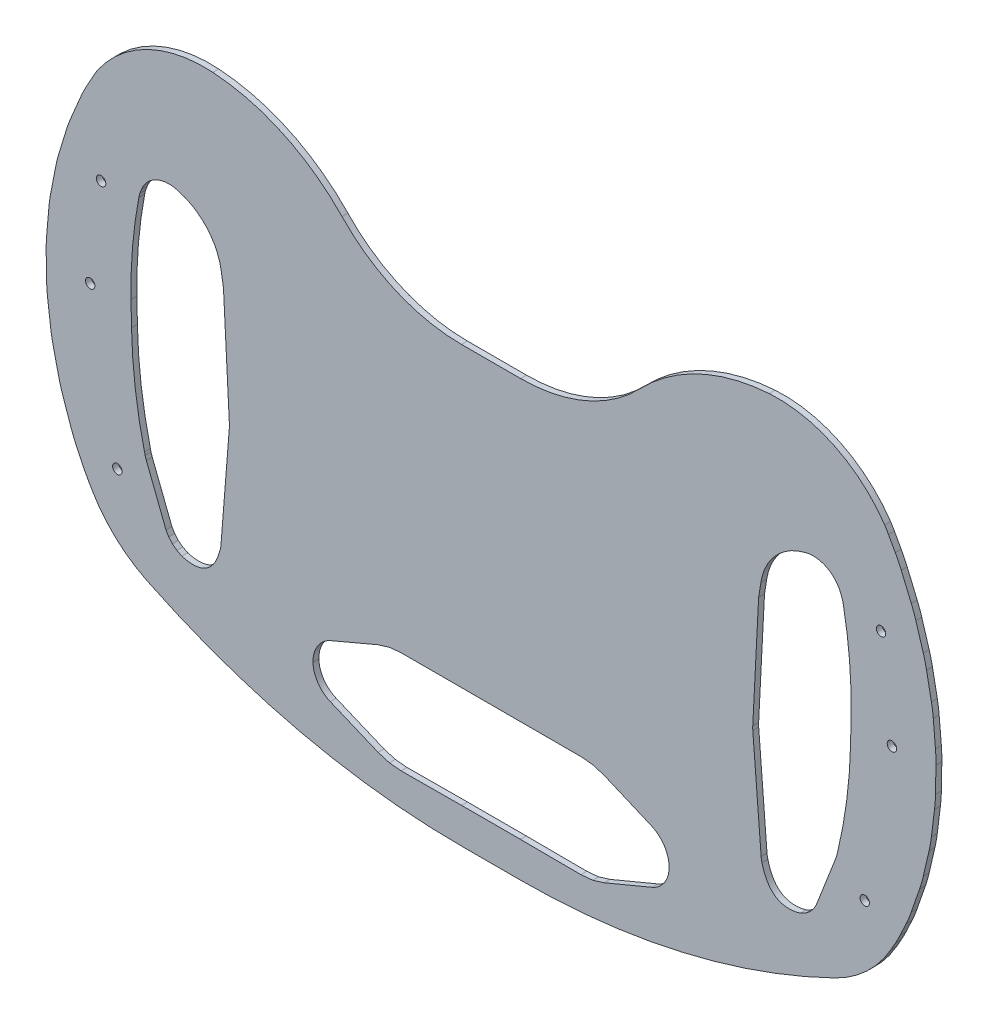
SolidWorks part; units mm, degrees
ref_plane "Front Plane" through (0, 0, 0) normal (0, 0, 1) x (1, 0, 0)
ref_plane "Top Plane" through (0, 0, 0) normal (0, 1, 0) x (1, 0, 0)
ref_plane "Right Plane" through (0, 0, 0) normal (1, 0, 0) x (0, 0, -1)
ref_plane "Plane1" through (0, 0, 3.5) normal (0, 0, -1) x (-1, 0, 0)
sketch "Sketch1" plane through (0, 0, 3.5) normal (0, 0, -1) x (-1, 0, 0)
  line L0 (-20, -102.6414) -> (0, -102.6414)
  line L1 (125.8777, -60.1203) -> (127.43, -57.3774)
  line L2 (129.0043, -54.3237) -> (131.0119, -50.025)
  line L3 (132.7446, -45.7413) -> (135.5927, -37.4764)
  line L4 (136.8602, -33.0625) -> (138.8158, -24.6128)
  line L5 (139.6165, -20.0899) -> (140.6803, -11.4846)
  line L6 (141.0053, -6.894) -> (141.1648, 1.7968)
  line L7 (141.0086, 6.3963) -> (140.2595, 15.0563)
  line L8 (139.6236, 19.6142) -> (137.9741, 28.1485)
  line L9 (136.8656, 32.6152) -> (134.3475, 40.8854)
  line L10 (132.7862, 45.1938) -> (129.381, 53.2529)
  line L11 (127.3612, 57.4098) -> (125.0649, 61.565)
  line L12 (0.0374, 44.9876) -> (-20.0374, 44.9876)
  line L13 (-145.0649, 61.565) -> (-147.3612, 57.4098)
  line L14 (-149.381, 53.2529) -> (-152.7862, 45.1938)
  line L15 (-154.3475, 40.8854) -> (-156.8656, 32.6152)
  line L16 (-157.9741, 28.1485) -> (-159.6236, 19.6142)
  line L17 (-160.2595, 15.0563) -> (-161.0086, 6.3963)
  line L18 (-161.1648, 1.7968) -> (-161.0053, -6.894)
  line L19 (-160.6803, -11.4846) -> (-159.6165, -20.0899)
  line L20 (-158.8158, -24.6128) -> (-156.8602, -33.0625)
  line L21 (-155.5927, -37.4764) -> (-152.7446, -45.7413)
  line L22 (-151.0119, -50.025) -> (-149.0043, -54.3237)
  line L23 (-147.43, -57.3774) -> (-145.8777, -60.1203)
  line L24 (44.6339, -82.422) -> (28.3718, -89.2144)
  line L25 (28.3718, -89.2144) -> (24.538, -90.3809)
  line L26 (24.538, -90.3809) -> (20.5478, -90.7594)
  line L27 (20.5478, -90.7594) -> (0, -90.6414)
  line L28 (0, -90.6414) -> (-20, -90.6414)
  line L29 (-20, -90.6414) -> (-40.5478, -90.7594)
  line L30 (-40.5478, -90.7594) -> (-44.538, -90.3809)
  line L31 (-44.538, -90.3809) -> (-48.3718, -89.2144)
  line L32 (-48.3718, -89.2144) -> (-64.6339, -82.422)
  line L33 (-64.4108, -64.3712) -> (-48.4626, -57.6021)
  line L34 (-48.4626, -57.6021) -> (-44.6356, -56.4136)
  line L35 (-44.6356, -56.4136) -> (-40.6476, -56.0122)
  line L36 (-40.6476, -56.0122) -> (20.6476, -56.0122)
  line L37 (20.6476, -56.0122) -> (24.6356, -56.4136)
  line L38 (24.6356, -56.4136) -> (28.4626, -57.6021)
  line L39 (28.4626, -57.6021) -> (44.4108, -64.3712)
  line L40 (112.3309, 2.0082) -> (112.1695, -6.1772)
  line L41 (107.758, -40.4653) -> (107.5331, -41.3997)
  line L42 (107.1259, -42.6965) -> (100.4528, -59.7886)
  line L43 (100.4528, -59.7886) -> (99.4938, -61.4077)
  line L44 (99.4938, -61.4077) -> (98.2496, -62.8189)
  line L45 (98.2496, -62.8189) -> (96.7623, -63.9722)
  line L46 (96.7623, -63.9722) -> (95.0856, -64.8257)
  line L47 (81.7649, -54.7734) -> (78.9349, -19.1114)
  line L48 (78.9168, -17.8071) -> (80.9084, 20.95)
  line L49 (80.9084, 20.95) -> (81.6792, 25.8111)
  line L50 (96.2559, 41.9974) -> (96.9265, 42.1771)
  line L51 (109.6658, 33.4984) -> (109.6817, 33.4149)
  line L52 (-129.6817, 33.4149) -> (-129.6658, 33.4984)
  line L53 (-116.9265, 42.1771) -> (-116.2559, 41.9974)
  line L54 (-101.6792, 25.8111) -> (-100.9084, 20.95)
  line L55 (-100.9084, 20.95) -> (-98.9168, -17.8071)
  line L56 (-98.9349, -19.1114) -> (-101.7649, -54.7734)
  line L57 (-115.0856, -64.8257) -> (-116.7623, -63.9722)
  line L58 (-116.7623, -63.9722) -> (-118.2496, -62.8189)
  line L59 (-118.2496, -62.8189) -> (-119.4938, -61.4077)
  line L60 (-119.4938, -61.4077) -> (-120.4528, -59.7886)
  line L61 (-120.4528, -59.7886) -> (-127.1259, -42.6965)
  line L62 (-127.5331, -41.3997) -> (-127.758, -40.4653)
  line L63 (-132.1695, -6.1772) -> (-132.3309, 2.0082)
  arc A0 (-126.8504, -78.0061) -> (-20, -102.6414) centre (-20, 141.3972) ccw
  arc A1 (0, -102.6414) -> (106.8504, -78.0061) centre (0, 141.3972) ccw
  arc A2 (106.8504, -78.0061) -> (125.8777, -60.1203) centre (87.5853, -38.4478) ccw
  arc A3 (127.43, -57.3774) -> (129.0043, -54.3237) centre (89.1377, -35.705) ccw
  arc A4 (131.0119, -50.025) -> (132.7446, -45.7413) centre (91.1453, -31.4063) ccw
  arc A5 (135.5927, -37.4764) -> (136.8602, -33.0625) centre (93.9933, -23.1414) ccw
  arc A6 (138.8158, -24.6128) -> (139.6165, -20.0899) centre (95.9489, -14.6918) ccw
  arc A7 (140.6803, -11.4846) -> (141.0053, -6.894) centre (97.0127, -6.0864) ccw
  arc A8 (141.1648, 1.7968) -> (141.0086, 6.3963) centre (97.1722, 2.6044) ccw
  arc A9 (140.2595, 15.0563) -> (139.6236, 19.6142) centre (96.4232, 11.2644) ccw
  arc A10 (137.9741, 28.1485) -> (136.8656, 32.6152) centre (94.7736, 19.7987) ccw
  arc A11 (134.3475, 40.8854) -> (132.7862, 45.1938) centre (92.2555, 28.0689) ccw
  arc A12 (129.381, 53.2529) -> (127.3612, 57.4098) centre (88.8503, 36.128) ccw
  arc A13 (125.0649, 61.565) -> (123.7376, 63.8075) centre (86.5541, 40.2833) ccw
  arc A14 (123.7376, 63.8075) -> (84.5336, 82.7977) centre (87.469, 38.8958) ccw
  arc A15 (84.5336, 82.7977) -> (40.6457, 62.3143) centre (89.0023, 15.9642) ccw
  arc A16 (40.6457, 62.3143) -> (0.0374, 44.9876) centre (0.0374, 101.2376) cw
  arc A17 (-20.0374, 44.9876) -> (-60.6457, 62.3143) centre (-20.0374, 101.2376) cw
  arc A18 (-60.6457, 62.3143) -> (-104.5336, 82.7977) centre (-109.0023, 15.9642) ccw
  arc A19 (-104.5336, 82.7977) -> (-143.7376, 63.8075) centre (-107.469, 38.8958) ccw
  arc A20 (-143.7376, 63.8075) -> (-145.0649, 61.565) centre (-106.5541, 40.2833) ccw
  arc A21 (-147.3612, 57.4098) -> (-149.381, 53.2529) centre (-108.8503, 36.128) ccw
  arc A22 (-152.7862, 45.1938) -> (-154.3475, 40.8854) centre (-112.2555, 28.0689) ccw
  arc A23 (-156.8656, 32.6152) -> (-157.9741, 28.1485) centre (-114.7736, 19.7987) ccw
  arc A24 (-159.6236, 19.6142) -> (-160.2595, 15.0563) centre (-116.4232, 11.2644) ccw
  arc A25 (-161.0086, 6.3963) -> (-161.1648, 1.7968) centre (-117.1722, 2.6044) ccw
  arc A26 (-161.0053, -6.894) -> (-160.6803, -11.4846) centre (-117.0127, -6.0864) ccw
  arc A27 (-159.6165, -20.0899) -> (-158.8158, -24.6128) centre (-115.9489, -14.6918) ccw
  arc A28 (-156.8602, -33.0625) -> (-155.5927, -37.4764) centre (-113.9933, -23.1414) ccw
  arc A29 (-152.7446, -45.7413) -> (-151.0119, -50.025) centre (-111.1453, -31.4063) ccw
  arc A30 (-149.0043, -54.3237) -> (-147.43, -57.3774) centre (-109.1377, -35.705) ccw
  arc A31 (-145.8777, -60.1203) -> (-126.8504, -78.0061) centre (-107.5853, -38.4478) ccw
  arc A32 (50.5015, -73.7885) -> (44.6339, -82.422) centre (40.9532, -73.6098) cw
  arc A33 (-64.6339, -82.422) -> (-70.5015, -73.7885) centre (-60.9532, -73.6098) cw
  arc A34 (-70.5015, -73.7885) -> (-70.5024, -73.7384) centre (-50.505, -73.4142) cw
  arc A35 (-70.5024, -73.7384) -> (-64.4108, -64.3712) centre (-60.5037, -73.5763) cw
  arc A36 (44.4108, -64.3712) -> (50.5024, -73.7384) centre (40.5037, -73.5763) cw
  arc A37 (50.5024, -73.7384) -> (50.5015, -73.7885) centre (30.505, -73.4142) cw
  arc A38 (109.6817, 33.4149) -> (112.3309, 2.0082) centre (-39.6396, 5.0043) cw
  arc A39 (112.1695, -6.1772) -> (107.758, -40.4653) centre (-47.7994, -3.0234) cw
  arc A40 (107.5331, -41.3997) -> (107.1259, -42.6965) centre (97.8107, -39.0596) cw
  arc A41 (82.0451, -56.4592) -> (81.7649, -54.7734) centre (91.7335, -53.9823) cw
  arc A42 (78.9349, -19.1114) -> (78.9168, -17.8071) centre (88.9036, -18.3203) cw
  arc A43 (81.6792, 25.8111) -> (96.2559, 41.9974) centre (101.4324, 22.6789) cw
  arc A44 (96.9265, 42.1771) -> (108.8049, 36.2185) centre (99.5148, 32.5179) cw
  arc A45 (108.8049, 36.2185) -> (109.3051, 34.8618) centre (81.8079, 25.4934) cw
  arc A46 (109.3051, 34.8618) -> (109.6658, 33.4984) centre (99.842, 31.6292) cw
  circle A47 centre (122.5079, 31.8736) radius 1.6
  circle A48 centre (126.214, -0.1264) radius 1.6
  circle A49 centre (116.9811, -50.1265) radius 1.6
  arc A50 (-132.3309, 2.0082) -> (-129.6817, 33.4149) centre (19.6396, 5.0043) cw
  arc A51 (-129.6658, 33.4984) -> (-129.3051, 34.8618) centre (-119.842, 31.6292) cw
  arc A52 (-128.8049, 36.2185) -> (-129.3051, 34.8618) centre (-101.8079, 25.4934) ccw
  arc A53 (-128.8049, 36.2185) -> (-116.9265, 42.1771) centre (-119.5148, 32.5179) cw
  arc A54 (-116.2559, 41.9974) -> (-101.6792, 25.8111) centre (-121.4324, 22.6789) cw
  arc A55 (-98.9168, -17.8071) -> (-98.9349, -19.1114) centre (-108.9036, -18.3203) cw
  arc A56 (-101.7649, -54.7734) -> (-102.0451, -56.4592) centre (-111.7335, -53.9823) cw
  arc A57 (-127.1259, -42.6965) -> (-127.5331, -41.3997) centre (-117.8107, -39.0596) cw
  arc A58 (-127.758, -40.4653) -> (-132.1695, -6.1772) centre (27.7994, -3.0234) cw
  circle A59 centre (-142.5079, 31.8736) radius 1.6
  circle A60 centre (-146.214, -0.1264) radius 1.6
  circle A61 centre (-136.9811, -50.1265) radius 1.6
  spline S0 degree 3 poles (95.0856, -64.8257) (88.312, -66.7584) (83.9652, -63.9696) (82.0451, -56.4592) knots 0 0 0 0 1 1 1 1
  spline S1 degree 3 poles (-115.0856, -64.8257) (-108.312, -66.7584) (-103.9652, -63.9696) (-102.0451, -56.4592) knots 0 0 0 0 1 1 1 1
extrude "Boss-Extrude1" add sketch "Sketch1" against normal blind 2
